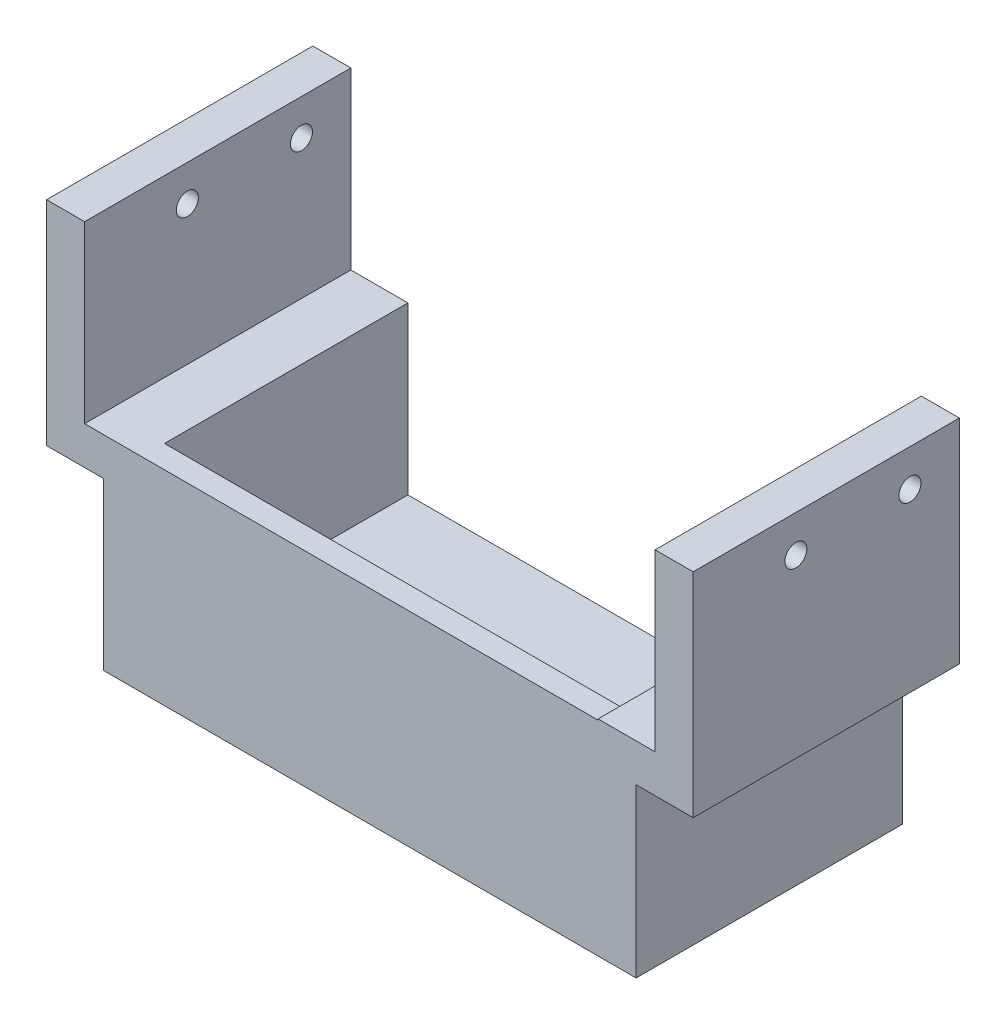
SolidWorks part; units mm, degrees
ref_plane "前基準面" through (0, 0, 0) normal (0, 0, 1) x (1, 0, 0)
ref_plane "上基準面" through (0, 0, 0) normal (0, 1, 0) x (1, 0, 0)
ref_plane "右基準面" through (0, 0, 0) normal (1, 0, 0) x (0, 0, -1)
sketch "草圖1" plane through (0, 0, 0) normal (0, 0, 1) x (1, 0, 0)
  line L0 (-21.2936, 10.1255) -> (-28.7936, 10.1255)
  line L1 (38.7064, 10.2677) -> (46.2064, 10.2677)
  line L2 (-21.2936, 10.1255) -> (-21.2936, -11.7323)
  line L3 (-21.2936, -11.7323) -> (38.7064, -11.7323)
  line L4 (38.7064, 10.2677) -> (38.7064, -11.7323)
  line L5 (-28.7936, 10.1255) -> (-28.7936, 33.1255)
  line L6 (46.2064, 10.2677) -> (46.2064, 33.2677)
  line L7 (-28.7936, 33.1255) -> (-33.7936, 33.1255)
  line L8 (-33.7936, 33.1255) -> (-33.7936, 5.1255)
  line L9 (-33.7936, 5.1255) -> (-26.2936, 5.1255)
  line L10 (-26.2936, 5.1255) -> (-26.2936, -16.7323)
  line L11 (-26.2936, -16.7323) -> (43.7064, -16.7323)
  line L12 (43.7064, -16.7323) -> (43.7064, 5.2677)
  line L13 (43.7064, 5.2677) -> (51.2064, 5.2677)
  line L14 (51.2064, 5.2677) -> (51.2064, 33.2677)
  line L15 (51.2064, 33.2677) -> (46.2064, 33.2677)
  dimension "D1" = 22
  dimension "D2" = 60
  dimension "D3" = 7.5
  dimension "D4" = 7.5
  dimension "D5" = 23
  dimension "D6" = 23
  dimension "D7" = 5
  dimension "D8" = 5
  dimension "D9" = 5
  dimension "D10" = 5
  dimension "D11" = 5
  dimension "D12" = 5
  dimension "D13" = 5
extrude "填料-伸長1" add sketch "草圖1" along normal blind 35 contours L0 L5 L7 L8 L9 L10 L11 L12 L13 L14 L15 L6 L1 L4 L3 L2
sketch "草圖2" plane through (0, 0, 35) normal (0, 0, 1) x (1, 0, 0)
  line L1 (51.2064, 10.1255) -> (51.2064, 5.2677)
  line L2 (51.2064, 5.2677) -> (43.7064, 5.2677)
  line L3 (43.7064, 5.2677) -> (43.7064, -16.7323)
  line L4 (43.7064, -16.7323) -> (-26.2936, -16.7323)
  line L5 (-26.2936, -16.7323) -> (-26.2936, 5.1255)
  line L6 (-26.2936, 5.1255) -> (-33.7936, 5.1255)
  line L7 (-33.7936, 5.1255) -> (-33.7936, 10.1255)
  line L8 (-33.7936, 10.1255) -> (51.2064, 10.1255)
extrude "填料-伸長2" add sketch "草圖2" against normal blind 3
sketch "草圖3" plane through (-33.7936, 0, 0) normal (-1, 0, 0) x (0, 0, 1)
  line L0 (35, 33.2677) -> (0, 33.2677) construction
  line L1 (35, 33.1255) -> (35, 5.1255) construction
  circle A0 centre (6.5, 28.4077) radius 1.45
  circle A1 centre (21.5, 28.4077) radius 1.45
  dimension "D1" = 2.9
  dimension "D2" = 2.9
  dimension "D3" = 4.86
  dimension "D4" = 15
  dimension "D5" = 4.86
  dimension "D6" = 13.5
extrude "除料-伸長1" cut sketch "草圖3" against normal through all contours A0 | A1
